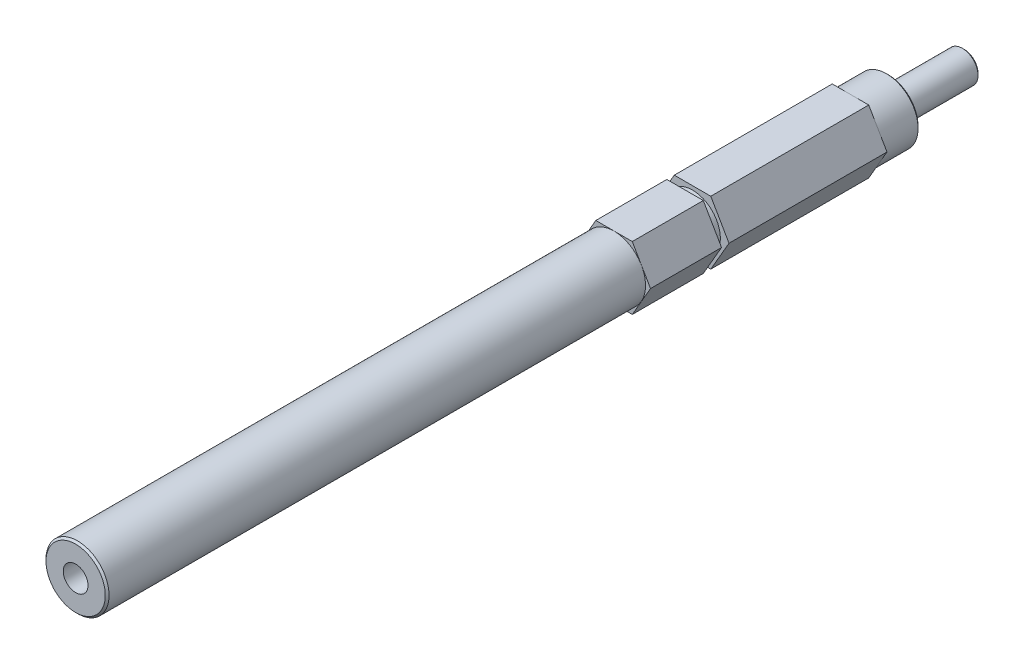
SolidWorks part; units mm, degrees
material "AISI 4130 Steel, annealed at 865C"
ref_plane "Front" through (0, 0, 0) normal (0, 0, 1) x (1, 0, 0)
ref_plane "Top" through (0, 0, 0) normal (0, 1, 0) x (1, 0, 0)
ref_plane "Right" through (0, 0, 0) normal (1, 0, 0) x (0, 0, -1)
ref_plane "Plane1" through (0, 0, 0) normal (0, 0, -1) x (-1, 0, 0)
sketch "Sketch1" plane through (0, 0, 0) normal (0, 0, -1) x (-1, 0, 0)
  line L0 (-16.3857, 0) -> (-12.7195, -6.35)
  line L1 (-12.7195, -6.35) -> (-5.3871, -6.35)
  line L2 (-5.3871, -6.35) -> (-1.721, 0)
  line L3 (-1.721, 0) -> (-5.3871, 6.35)
  line L4 (-5.3871, 6.35) -> (-12.7195, 6.35)
  line L5 (-12.7195, 6.35) -> (-16.3857, 0)
extrude "Boss-Extrude1" add sketch "Sketch1" against normal blind 31.75
sketch "Sketch2" plane through (0, 0, 31.75) normal (0, 0, 1) x (1, 0, 0)
  circle A0 centre (9.0533, 0) radius 5.588
extrude "Boss-Extrude2" add sketch "Sketch2" along normal blind 1.4986
ref_plane "Plane2" through (0, 0, 33.2486) normal (0, 0, -1) x (-1, 0, 0)
sketch "Sketch3" plane through (0, 0, 33.2486) normal (0, 0, -1) x (-1, 0, 0)
  line L0 (-12.7195, -6.35) -> (-5.3871, -6.35)
  line L1 (-5.3871, -6.35) -> (-1.721, 0)
  line L2 (-1.721, 0) -> (-5.3871, 6.35)
  line L3 (-5.3871, 6.35) -> (-12.7195, 6.35)
  line L4 (-12.7195, 6.35) -> (-16.3857, 0)
  line L5 (-16.3857, 0) -> (-12.7195, -6.35)
extrude "Boss-Extrude3" add sketch "Sketch3" against normal blind 14.2748
sketch "Sketch4" plane through (0, 0, 47.5234) normal (0, 0, 1) x (1, 0, 0)
  circle A0 centre (9.0533, 0) radius 6.3373
extrude "Boss-Extrude4" add sketch "Sketch4" along normal blind 108.204
ref_plane "Plane3" through (0, -4.699, 0) normal (0, 1, 0) x (-1, 0, 0)
sketch "Sketch5" plane through (0, -4.699, 0) normal (0, 1, 0) x (-1, 0, 0)
  line L0 (-7.4277, 59.2074) -> (-7.4277, 153.1874)
  line L1 (-10.6789, 153.1874) -> (-10.6789, 59.2074)
  arc A0 (-10.6789, 59.2074) -> (-7.4277, 59.2074) centre (-9.0533, 59.2074) ccw
  arc A1 (-7.4277, 153.1874) -> (-10.6789, 153.1874) centre (-9.0533, 153.1874) ccw
ref_plane "Plane4" through (0, 0, 0) normal (0, -1, 0) x (1, 0, 0)
sketch "Sketch6" plane through (0, 0, 0) normal (0, -1, 0) x (1, 0, 0)
  line L0 (15.397, 0) -> (9.0533, 0)
  line L1 (9.0533, 0) -> (9.0533, -22.86)
  line L2 (9.0533, -22.86) -> (12.2029, -22.86)
  line L3 (12.2029, -22.86) -> (12.2029, -7.62)
  line L4 (12.2029, -7.62) -> (15.397, -7.62)
  line L5 (15.397, -7.62) -> (15.397, 0)
  line L6 (9.0533, 0) -> (9.0533, -22.86) construction
revolve "Revolve1" add sketch "Sketch6" angle 360 about L6
hole_wizard "Hole1" positions "Sketch8" profile "Sketch7" legacy
sketch "Sketch8" plane through (0, 0, 155.7274) normal (0, 0, 1) x (1, 0, 0)
  point P0 (9.0533, 0)
sketch "Sketch7" plane through (9.0533, 0, 155.7274) normal (1, 0, 0) x (0, -1, 0)
  line L0 (0, 0) -> (0, 15.875)
  line L1 (0, 15.875) -> (2.4879, 15.875)
  line L2 (2.4879, 15.875) -> (2.4879, 0)
  line L3 (2.4879, 0) -> (0, 0)
  line L4 (0, 110) -> (0, -10) construction
  dimension "Diameter" = 4.9759
  dimension "Depth" = 15.875
chamfer "Chamfer1" distance 0.381 angle 45 1 edges at (2.7097, 0, -7.62)
chamfer "Chamfer2" distance 0.381 angle 45 1 edges at (15.3906, 0, 155.7274)
chamfer "Chamfer3" distance 0.381 angle 45 1 edges at (5.9037, 0, -22.86)
extrude "Cut-Extrude2" cut sketch "Sketch5" against normal blind 2.54
